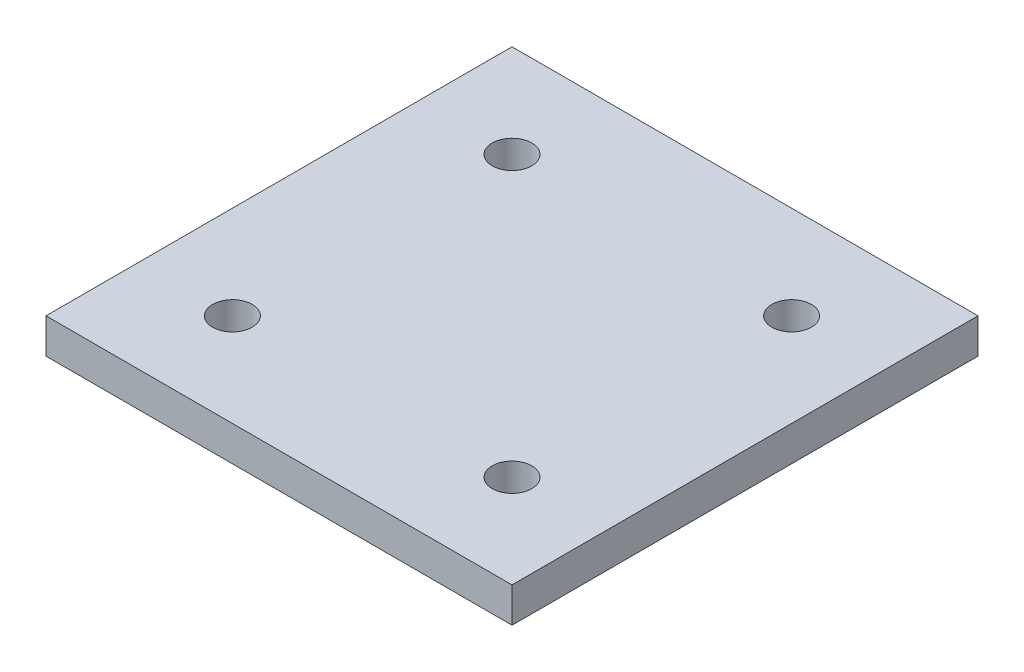
SolidWorks part; units mm, degrees
ref_plane "Front Plane" through (0, 0, 0) normal (0, 0, 1) x (1, 0, 0)
ref_plane "Top Plane" through (0, 0, 0) normal (0, 1, 0) x (1, 0, 0)
ref_plane "Right Plane" through (0, 0, 0) normal (1, 0, 0) x (0, 0, -1)
sketch "Sketch1" plane through (0, 0, 0) normal (0, 1, 0) x (1, 0, 0)
  line L1 (-20, -20) -> (20, -20)
  line L2 (-20, -20) -> (-20, 20)
  line L3 (-20, 20) -> (20, 20)
  line L4 (20, -20) -> (20, 20)
extrude "Cross Joiner" add sketch "Sketch1" along normal blind 3
sketch "Sketch2" plane through (0, 0, 0) normal (0, 1, 0) x (1, 0, 0)
  circle A0 centre (-12, -12) radius 1.7
  circle A1 centre (-12, 12) radius 1.7
  circle A2 centre (12, -12) radius 1.7
  circle A3 centre (12, 12) radius 1.7
extrude "Bolt Holes" cut sketch "Sketch2" against normal through all and the other way through all
